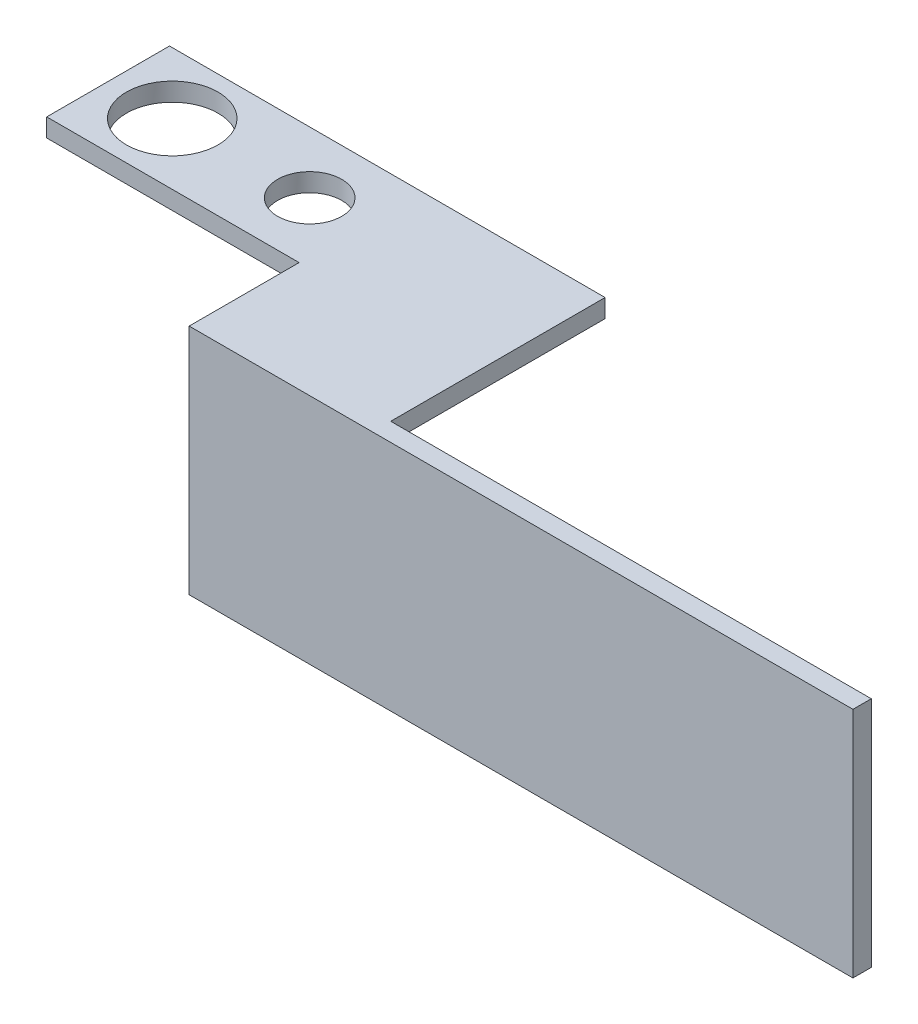
SolidWorks part; units mm, degrees
ref_plane "Alzado" through (0, 0, 0) normal (0, 0, 1) x (1, 0, 0)
ref_plane "Planta" through (0, 0, 0) normal (0, 1, 0) x (1, 0, 0)
ref_plane "Vista lateral" through (0, 0, 0) normal (1, 0, 0) x (0, 0, -1)
sketch "Croquis2" plane through (0, 0, 0) normal (1, 0, 0) x (0, 0, -1)
  line L1 (0, 0) -> (-21.4, 0)
  line L4 (-21.4, 0) -> (-21.4, -21.4)
  line L6 (-23.4, 2) -> (-23.4, -23.4)
  line L7 (2, 2) -> (-23.4, 2)
  line L8 (2, 2) -> (2, -23.4) construction
  line L9 (0, 0) -> (0, -21.4) construction
  line L10 (0, -21.4) -> (-21.4, -21.4) construction
  line L11 (2, -23.4) -> (-23.4, -23.4) construction
  line L12 (-23.4, -23.4) -> (-21.4, -23.4)
  line L13 (-21.4, -23.4) -> (-21.4, -21.4)
  line L14 (0, 0) -> (2, 0)
  line L15 (2, 0) -> (2, 2)
  dimension "D2" = 25.4
  dimension "D3" = 25.4
  dimension "D1" = 2
extrude "Saliente-Extruir1" add sketch "Croquis2" along normal blind 100 contours L1 L4 L13 L12 L6 L7 L15 L14
sketch "Croquis3" plane through (0, 2, 0) normal (0, 1, 0) x (1, 0, 0)
  line L0 (7, -4.7) -> (22, -4.7) construction
  line L1 (27.5479, -21.4) -> (47.5479, -21.4) construction
  line L3 (0, 2) -> (0, -11.4) construction
  line L4 (100, 2) -> (47.5479, 2)
  line L5 (100, 2) -> (100, -21.4)
  line L6 (100, -21.4) -> (47.5479, -21.4)
  line L7 (47.5479, 2) -> (47.5479, -21.4)
  line L8 (0, -21.4) -> (27.5479, -21.4) construction
  line L9 (0, -21.4) -> (0, -11.4)
  line L10 (0, -11.4) -> (27.5479, -11.4)
  line L11 (27.5479, -21.4) -> (27.5479, -11.4)
  line L13 (27.5479, -21.4) -> (27.5479, -23.4)
  line L14 (27.5479, -23.4) -> (0, -23.4)
  line L15 (0, -21.4) -> (0, -23.4)
  line L16 (0, -4.7) -> (7, -4.7) construction
  circle A0 centre (7, -4.7) radius 5
  circle A1 centre (22, -4.7) radius 3.5
  dimension "D4" = 15
  dimension "D5" = 7
  dimension "D1" = 10
  dimension "D2" = 20
  dimension "D3" = 7
extrude "Cortar-Extruir1" cut sketch "Croquis3" against normal up to surface (2 mm away) up to face at (50, 0, 9.7)
sketch "Croquis4" plane through (0, 0, 21.4) normal (0, 0, -1) x (-1, 0, 0)
  line L1 (0, -23.4) -> (-27.5479, -23.4)
  line L2 (0, -23.4) -> (0, 0)
  line L3 (0, 0) -> (-27.5479, 0)
  line L4 (-27.5479, -23.4) -> (-27.5479, 0)
extrude "Cortar-Extruir2" cut sketch "Croquis4" against normal up to next
